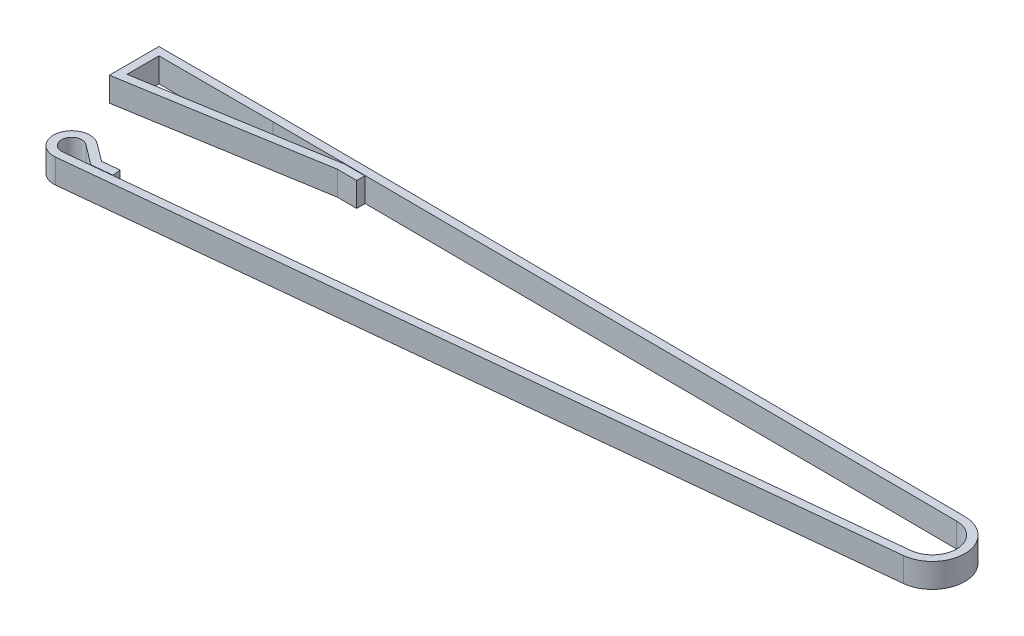
SolidWorks part; units mm, degrees
ref_plane "Front Plane" through (0, 0, 0) normal (0, 0, 1) x (1, 0, 0)
ref_plane "Top Plane" through (0, 0, 0) normal (0, 1, 0) x (1, 0, 0)
ref_plane "Right Plane" through (0, 0, 0) normal (1, 0, 0) x (0, 0, -1)
sketch "Sketch1" plane through (0, 49.4, 0) normal (0, 1, 0) x (1, 0, 0)
  line L0 (-76.2248, -18) -> (-104.4248, -18)
  line L1 (-104.4248, -18) -> (-104.4248, -25.9)
  line L2 (93.9301, -19.0001) -> (-76.2248, -18)
  line L3 (-95.7449, -50.4869) -> (94.5072, -30.9687)
  line L4 (-104.4248, -25.9) -> (-58.2584, -18.2056)
  line L5 (-58.2584, -18.2056) -> (-53.2584, -18.235)
  line L6 (-104.4248, -25.9) -> (-76.2248, -21.2) construction
  line L7 (-94.4955, -46.0033) -> (-89.5253, -49.7484)
  line L8 (-89.5253, -49.7484) -> (-84.5514, -49.2381)
  circle A4 centre (93.8949, -25) radius 6 construction
  arc A6 (-98.5, -48) -> (-93.5, -48) centre (-96, -48) ccw construction
  arc A7 (93.9301, -19.0001) -> (94.5072, -30.9687) centre (93.8949, -25) cw
  circle A8 centre (-96, -48) radius 2.5 construction
  arc A9 (-95.7449, -50.4869) -> (-94.4955, -46.0033) centre (-96, -48) cw
  dimension "D1" = 5
  dimension "D2" = 0.1
  dimension "D3" = 5
  dimension "D4" = 0.1
extrude "Extrude-Thin1" add sketch "Sketch1" along normal mid plane 6 thin
